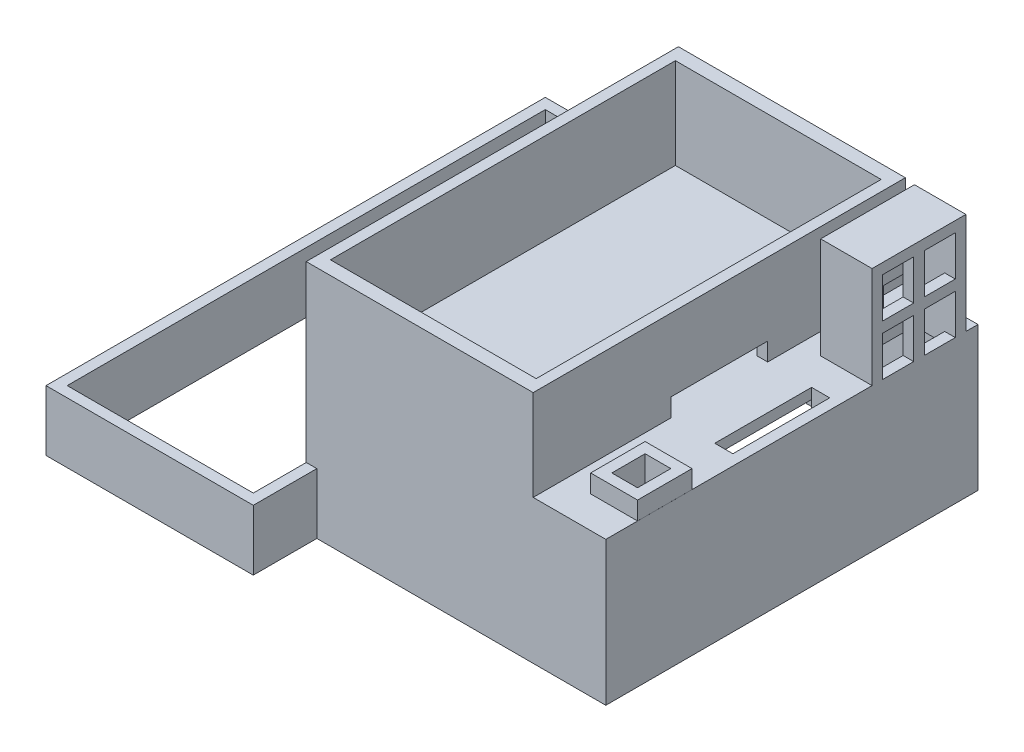
SolidWorks part; units mm, degrees
ref_plane "Front Plane" through (0, 0, 0) normal (0, 0, 1) x (1, 0, 0)
ref_plane "Top Plane" through (0, 0, 0) normal (0, 1, 0) x (1, 0, 0)
ref_plane "Right Plane" through (0, 0, 0) normal (1, 0, 0) x (0, 0, -1)
sketch "Sketch1" plane through (0, 0, 0) normal (0, 1, 0) x (1, 0, 0)
  line L1 (-138.162, -76.1412) -> (-88.662, -76.1412)
  line L2 (-138.162, -76.1412) -> (-138.162, -14.6412)
  line L3 (-138.162, -14.6412) -> (-88.662, -14.6412)
  line L4 (-88.662, -76.1412) -> (-88.662, -14.6412)
  dimension "D1" = 49.5
  dimension "D2" = 61.5
extrude "Boss-Extrude1" add sketch "Sketch1" along normal blind 23.75
sketch "Sketch2" plane through (0, 0, 0) normal (0, -1, 0) x (-1, 0, 0)
  line L0 (138.162, -76.1412) -> (88.662, -76.1412) construction
  line L1 (90.412, -74.3912) -> (136.412, -74.3912)
  line L2 (90.412, -74.3912) -> (90.412, -16.3912)
  line L3 (90.412, -16.3912) -> (136.412, -16.3912)
  line L4 (136.412, -74.3912) -> (136.412, -16.3912)
  line L5 (88.662, -76.1412) -> (88.662, -14.6412) construction
  line L6 (88.662, -14.6412) -> (138.162, -14.6412) construction
  line L7 (138.162, -14.6412) -> (138.162, -76.1412) construction
  dimension "D1" = 1.75
  dimension "D2" = 1.75
  dimension "D3" = 1.75
  dimension "D4" = 1.75
extrude "Cut-Extrude1" cut sketch "Sketch2" against normal blind 22
sketch "Sketch3" plane through (0, 22, 0) normal (0, -1, 0) x (-1, 0, 0)
  line L0 (136.412, -16.3912) -> (90.412, -16.3912) construction
  line L1 (90.412, -74.3912) -> (93.412, -74.3912)
  line L2 (90.412, -74.3912) -> (90.412, -16.3912)
  line L3 (90.412, -16.3912) -> (93.412, -16.3912)
  line L4 (93.412, -74.3912) -> (93.412, -16.3912)
  line L6 (90.412, -58.3912) -> (93.412, -58.3912)
  line L7 (90.412, -58.3912) -> (90.412, -53.3912)
  line L8 (90.412, -53.3912) -> (93.412, -53.3912)
  line L9 (93.412, -58.3912) -> (93.412, -53.3912)
  line L10 (90.412, -37.3912) -> (93.412, -37.3912)
  line L11 (90.412, -37.3912) -> (90.412, -32.3912)
  line L12 (90.412, -32.3912) -> (93.412, -32.3912)
  line L13 (93.412, -37.3912) -> (93.412, -32.3912)
  line M9 (90.412, -16.3912) -> (90.412, -74.3912)
  line M10 (90.412, -74.3912) -> (136.412, -74.3912)
  line M12 (136.412, -16.3912) -> (90.412, -16.3912)
  dimension "D1" = 3
  dimension "D2" = 5
  dimension "D3" = 5
  dimension "D4" = 16
  dimension "D5" = 16
extrude "Cut-Extrude2" cut sketch "Sketch3" against normal blind 1.75 contours L6 L2 L4 M10 | L12 L4 M9 M12 | L10 L2 L8 L4
sketch "Sketch7" plane through (0, 22, 0) normal (0, -1, 0) x (-1, 0, 0)
  line L1 (90.412, -58.3912) -> (93.412, -58.3912)
  line L2 (90.412, -58.3912) -> (90.412, -53.3912)
  line L3 (90.412, -53.3912) -> (93.412, -53.3912)
  line L4 (93.412, -58.3912) -> (93.412, -53.3912)
  line L5 (90.412, -37.3912) -> (93.412, -37.3912)
  line L6 (90.412, -37.3912) -> (90.412, -32.3912)
  line L7 (90.412, -32.3912) -> (93.412, -32.3912)
  line L8 (93.412, -37.3912) -> (93.412, -32.3912)
  point P10 (91.4714, -46.0867)
extrude "Boss-Extrude2" add sketch "Sketch7" along normal blind 4 contours L2 L1 L4 L3 | L6 L5 L8 L7
sketch "Sketch9" plane through (-93.412, 0, 0) normal (-1, 0, 0) x (0, 0, 1)
  line L0 (58.3912, 18) -> (58.3912, 22) construction
  line L1 (58.3912, 20.407) -> (53.3912, 20.407)
  line L2 (58.3912, 20.407) -> (58.3912, 22)
  line L3 (58.3912, 22) -> (53.3912, 22)
  line L4 (53.3912, 20.407) -> (53.3912, 22)
  point P7 (52.9928, 22.2027)
sketch "Sketch11" plane through (0, 23.75, 0) normal (0, 1, 0) x (1, 0, 0)
  line L0 (-138.162, -76.1412) -> (-88.662, -76.1412) construction
  line L1 (-138.162, -14.6412) -> (-100.662, -14.6412)
  line L2 (-138.162, -14.6412) -> (-138.162, -76.1412)
  line L3 (-138.162, -76.1412) -> (-100.662, -76.1412)
  line L4 (-100.662, -14.6412) -> (-100.662, -76.1412)
  dimension "D1" = 37.5
extrude "Boss-Extrude3" add sketch "Sketch11" along normal blind 15
sketch "Sketch12" plane through (0, 38.75, 0) normal (0, 1, 0) x (1, 0, 0)
  line L0 (-138.162, -14.6412) -> (-138.162, -76.1412) construction
  line L1 (-136.412, -16.8912) -> (-102.412, -16.8912)
  line L2 (-136.412, -16.8912) -> (-136.412, -73.8912)
  line L3 (-136.412, -73.8912) -> (-102.412, -73.8912)
  line L4 (-102.412, -16.8912) -> (-102.412, -73.8912)
  line L5 (-100.662, -76.1412) -> (-100.662, -14.6412) construction
  line L6 (-100.662, -14.6412) -> (-138.162, -14.6412) construction
  line L7 (-138.162, -76.1412) -> (-100.662, -76.1412) construction
  dimension "D1" = 1.75
  dimension "D2" = 1.75
  dimension "D3" = 2.25
  dimension "D4" = 2.25
extrude "Cut-Extrude3" cut sketch "Sketch12" against normal blind 15
sketch "Sketch14" plane through (0, 23.75, 0) normal (0, 1, 0) x (1, 0, 0)
  line L0 (-90.412, -58.3912) -> (-93.412, -58.3912) construction
  line L1 (-96.417, -70.8912) -> (-88.667, -70.8912)
  line L2 (-96.417, -70.8912) -> (-96.417, -61.8912)
  line L3 (-96.417, -61.8912) -> (-88.667, -61.8912)
  line L4 (-88.667, -70.8912) -> (-88.667, -61.8912)
  point P6 (-91.912, -58.3912)
  dimension "D1" = 9
  dimension "D2" = 7.75
  dimension "D3" = 3.5
  dimension "D4" = 3.245
extrude "Boss-Extrude4" add sketch "Sketch14" along normal blind 3
sketch "Sketch15" plane through (0, 26.75, 0) normal (0, 1, 0) x (1, 0, 0)
  line L0 (-96.417, -61.8912) -> (-96.417, -70.8912) construction
  line L1 (-94.667, -69.1412) -> (-90.417, -69.1412)
  line L2 (-94.667, -69.1412) -> (-94.667, -63.6412)
  line L3 (-94.667, -63.6412) -> (-90.417, -63.6412)
  line L4 (-90.417, -69.1412) -> (-90.417, -63.6412)
  line L5 (-88.667, -61.8912) -> (-96.417, -61.8912) construction
  line L6 (-88.667, -70.8912) -> (-88.667, -61.8912) construction
  line L7 (-96.417, -70.8912) -> (-88.667, -70.8912) construction
  dimension "D1" = 1.75
  dimension "D2" = 1.75
  dimension "D3" = 1.75
  dimension "D4" = 1.75
extrude "Cut-Extrude4" cut sketch "Sketch15" against normal blind 4.75
sketch "Sketch16" plane through (0, 23.75, 0) normal (0, 1, 0) x (1, 0, 0)
  line L0 (-93.412, -16.3912) -> (-90.412, -16.3912) construction
  line L1 (-97.162, -32.1412) -> (-88.662, -32.1412)
  line L2 (-97.162, -32.1412) -> (-97.162, -16.6412)
  line L3 (-97.162, -16.6412) -> (-88.662, -16.6412)
  line L4 (-88.662, -32.1412) -> (-88.662, -16.6412)
  line L5 (-93.412, -32.3912) -> (-93.412, -16.3912) construction
  point P6 (-91.912, -16.3912)
  point P9 (-93.412, -24.3912)
  dimension "D1" = 15.5
  dimension "D2" = 8.5
  dimension "D3" = 3.25
  dimension "D4" = 7.75
extrude "Boss-Extrude5" add sketch "Sketch16" along normal blind 16.75
sketch "Sketch17" plane through (-88.662, 0, 0) normal (1, 0, 0) x (0, 0, -1)
  line L0 (-32.1412, 40.5) -> (-16.6412, 40.5) construction
  line L1 (-30.3912, 38.75) -> (-25.2662, 38.75)
  line L2 (-30.3912, 38.75) -> (-30.3912, 23.75)
  line L3 (-30.3912, 23.75) -> (-25.2662, 23.75)
  line L4 (-25.2662, 38.75) -> (-25.2662, 23.75)
  line L5 (-23.5162, 38.75) -> (-18.3912, 38.75)
  line L6 (-23.5162, 38.75) -> (-23.5162, 23.75)
  line L7 (-23.5162, 23.75) -> (-18.3912, 23.75)
  line L8 (-18.3912, 38.75) -> (-18.3912, 23.75)
  line L9 (-32.1412, 40.5) -> (-32.1412, 23.75) construction
  line L10 (-16.6412, 40.5) -> (-16.6412, 23.75) construction
  line L11 (-16.6412, 23.75) -> (-14.6412, 23.75) construction
  line L12 (-76.1412, 23.75) -> (-32.1412, 23.75) construction
  line L14 (-32.1412, 32.125) -> (-16.6412, 32.125)
  line L15 (-32.1412, 32.125) -> (-32.1412, 30.375)
  line L16 (-32.1412, 30.375) -> (-16.6412, 30.375)
  line L17 (-16.6412, 32.125) -> (-16.6412, 30.375)
  point P18 (-33.1974, 25.9347)
  dimension "D1" = 1.75
  dimension "D2" = 1.75
  dimension "D3" = 1.75
  dimension "D4" = 1.75
  dimension "D5" = 0
  dimension "D6" = 0
  dimension "D7" = 5.125
  dimension "D8" = 5.125
  dimension "D9" = 1.75
  dimension "D10" = 6.625
extrude "Cut-Extrude5" cut sketch "Sketch17" against normal blind 8.5 contours L2 L14 L4 L1 | L16 L2 L3 L4 | L6 L14 L8 L5 | L16 L6 L7 L8
sketch "Sketch18" plane through (0, 23.75, 0) normal (0, 1, 0) x (1, 0, 0)
  line L0 (-93.412, -18.3912) -> (-90.412, -18.3912) construction
  line L1 (-95.412, -30.3912) -> (-90.412, -30.3912)
  line L2 (-95.412, -30.3912) -> (-95.412, -18.3912)
  line L3 (-95.412, -18.3912) -> (-90.412, -18.3912)
  line L4 (-90.412, -30.3912) -> (-90.412, -18.3912)
  line L5 (-88.662, -30.3912) -> (-88.662, -25.2662) construction
  line L6 (-93.412, -30.3912) -> (-90.412, -30.3912) construction
  point P4 (-86.5623, -17.3867)
  dimension "D1" = 0
  dimension "D2" = 1.75
  dimension "D3" = 1.75
  dimension "D4" = 0
extrude "Cut-Extrude6" cut sketch "Sketch18" against normal blind 1.75 and the other way blind 15
sketch "Sketch20" plane through (-100.662, 0, 0) normal (1, 0, 0) x (0, 0, -1)
  line L0 (-76.1412, 23.75) -> (-14.6412, 23.75) construction
  line L1 (-53.3912, 26.75) -> (-37.3912, 26.75)
  line L2 (-53.3912, 26.75) -> (-53.3912, 23.75)
  line L3 (-53.3912, 23.75) -> (-37.3912, 23.75)
  line L4 (-37.3912, 26.75) -> (-37.3912, 23.75)
  dimension "D1" = 3
  dimension "D2" = 0
  dimension "D3" = 0
extrude "Cut-Extrude7" cut sketch "Sketch20" against normal blind 1.75
sketch "Sketch21" plane through (0, 0, 0) normal (0, -1, 0) x (-1, 0, 0)
  line L0 (138.162, -14.6412) -> (138.162, -76.1412) construction
  line L1 (136.412, -86.6412) -> (170.662, -86.6412)
  line L2 (136.412, -86.6412) -> (136.412, -4.1412)
  line L3 (136.412, -4.1412) -> (170.662, -4.1412)
  line L4 (170.662, -86.6412) -> (170.662, -4.1412)
  line L5 (138.162, -76.1412) -> (88.662, -76.1412) construction
  line L6 (88.662, -14.6412) -> (138.162, -14.6412) construction
  dimension "D1" = 32.5
  dimension "D2" = 1.75
  dimension "D3" = 10.5
  dimension "D4" = 10.5
extrude "Boss-Extrude7" add sketch "Sketch21" against normal blind 10
sketch "Sketch23" plane through (0, 10, 0) normal (0, 1, 0) x (1, 0, 0)
  line L0 (-136.412, -86.6412) -> (-170.662, -86.6412) construction
  line L1 (-138.162, -84.8912) -> (-168.912, -84.8912)
  line L2 (-138.162, -84.8912) -> (-138.162, -5.8912)
  line L3 (-138.162, -5.8912) -> (-168.912, -5.8912)
  line L4 (-168.912, -84.8912) -> (-168.912, -5.8912)
  line L5 (-170.662, -86.6412) -> (-170.662, -4.1412) construction
  line L6 (-170.662, -4.1412) -> (-136.412, -4.1412) construction
  line L7 (-138.162, -14.6412) -> (-138.162, -76.1412) construction
  dimension "D1" = 1.75
  dimension "D2" = 1.75
  dimension "D3" = 1.75
  dimension "D4" = 0
extrude "Cut-Extrude8" cut sketch "Sketch23" against normal blind 10
sketch "Sketch24" plane through (0, 23.75, 0) normal (0, -1, 0) x (-1, 0, 0)
  line L1 (93.383, -63.5335) -> (90.412, -63.5335)
  line L2 (93.383, -63.5335) -> (93.383, -58.3912)
  line L3 (93.383, -58.3912) -> (90.412, -58.3912)
  line L4 (90.412, -63.5335) -> (90.412, -58.3912)
  point P4 (90.2168, -58.8512)
  point P5 (92.4145, -61.2254)
  point P7 (92.438, -62.7965)
sketch "Sketch25" plane through (0, 22, 0) normal (0, -1, 0) x (-1, 0, 0)
  line L0 (90.412, -63.5335) -> (90.412, -58.3912) construction
  line L1 (93.412, -63.6412) -> (90.412, -63.6412)
  line L2 (93.412, -63.6412) -> (93.412, -58.3912)
  line L3 (93.412, -58.3912) -> (90.412, -58.3912)
  line L4 (90.412, -63.6412) -> (90.412, -58.3912)
  line L5 (93.383, -58.3912) -> (90.412, -58.3912) construction
  line L6 (93.412, -74.3912) -> (136.412, -74.3912) construction
  line L7 (93.412, -69.1412) -> (90.412, -69.1412)
  line L8 (93.412, -69.1412) -> (93.412, -74.3912)
  line L9 (93.412, -74.3912) -> (90.412, -74.3912)
  line L10 (90.412, -69.1412) -> (90.412, -74.3912)
  line L11 (90.412, -70.8912) -> (90.412, -61.8912) construction
  dimension "D1" = 0
  dimension "D2" = 0
  dimension "D3" = 0
  dimension "D4" = 0
extrude "Boss-Extrude8" add sketch "Sketch25" against normal blind 1.75
sketch "Sketch26" plane through (0, 23.75, 0) normal (0, 1, 0) x (1, 0, 0)
  line L1 (-93.412, -32.3912) -> (-90.412, -32.3912)
  line L2 (-93.412, -32.3912) -> (-93.412, -30.3912)
  line L3 (-93.412, -30.3912) -> (-90.412, -30.3912)
  line L4 (-90.412, -32.3912) -> (-90.412, -30.3912)
  point P4 (-90.1907, -29.1847)
sketch "Sketch28" plane through (0, 23.75, 0) normal (0, 1, 0) x (1, 0, 0)
  line L0 (-90.412, -23.5162) -> (-90.412, -18.3912) construction
  line L1 (-93.412, -16.3912) -> (-90.412, -16.3912)
  line L2 (-93.412, -16.3912) -> (-93.412, -18.3912)
  line L3 (-93.412, -18.3912) -> (-90.412, -18.3912)
  line L4 (-90.412, -16.3912) -> (-90.412, -18.3912)
  line L6 (-90.412, -32.3912) -> (-93.412, -32.3912)
  line L7 (-90.412, -32.3912) -> (-90.412, -30.3912)
  line L8 (-90.412, -30.3912) -> (-93.412, -30.3912)
  line L9 (-93.412, -32.3912) -> (-93.412, -30.3912)
  point P7 (-92.9195, -29.7842)
extrude "Boss-Extrude9" add sketch "Sketch28" against normal blind 1.75
